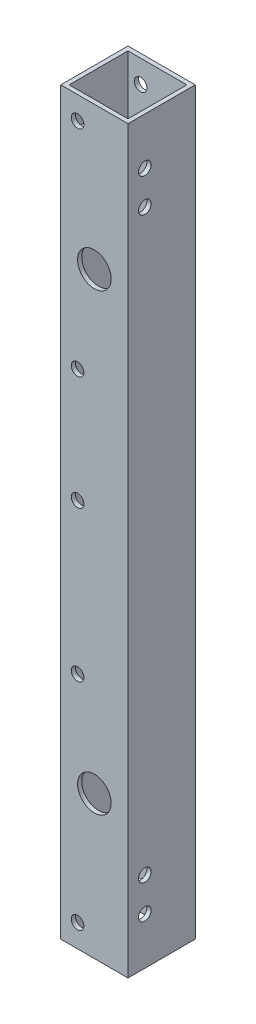
SolidWorks part; units mm, degrees
material "6061-T4 (SS)"
ref_plane "Front Plane" through (0, 0, 0) normal (0, 0, 1) x (1, 0, 0)
ref_plane "Top Plane" through (0, 0, 0) normal (0, 1, 0) x (1, 0, 0)
ref_plane "Right Plane" through (0, 0, 0) normal (1, 0, 0) x (0, 0, -1)
sketch "Sketch1" plane through (0, 0, 0) normal (0, 0, 1) x (1, 0, 0)
  line L1 (63.386, 102.0504) -> (88.786, 102.0504)
  line L2 (63.386, 102.0504) -> (63.386, -177.3496)
  line L3 (63.386, -177.3496) -> (88.786, -177.3496)
  line L4 (88.786, 102.0504) -> (88.786, -177.3496)
  dimension "D1" = 279.4
  dimension "D2" = 25.4
extrude "Boss-Extrude1" add sketch "Sketch1" along normal blind 25.4
sketch "Sketch2" plane through (0, 102.0504, 0) normal (0, 1, 0) x (1, 0, 0)
  line L0 (63.386, -25.4) -> (63.386, 0) construction
  line L1 (64.9735, -23.8125) -> (87.1985, -23.8125)
  line L2 (64.9735, -23.8125) -> (64.9735, -1.5875)
  line L3 (64.9735, -1.5875) -> (87.1985, -1.5875)
  line L4 (87.1985, -23.8125) -> (87.1985, -1.5875)
  line L5 (88.786, -25.4) -> (88.786, 0) construction
  line L6 (88.786, -25.4) -> (63.386, -25.4) construction
  line L7 (88.786, 0) -> (63.386, 0) construction
  dimension "D1" = 1.5875
  dimension "D2" = 1.5875
  dimension "D3" = 1.5875
  dimension "D4" = 1.5875
extrude "Cut-Extrude1" cut sketch "Sketch2" against normal blind 279.4
sketch "Sketch3" plane through (0, 0, 0) normal (0, 0, -1) x (-1, 0, 0)
  line L0 (-88.786, 102.0504) -> (-63.386, 102.0504) construction
  line L1 (-63.386, -177.3496) -> (-88.786, -177.3496) construction
  line L2 (-88.786, -177.3496) -> (-88.786, 102.0504) construction
  circle A0 centre (-76.086, 48.0754) radius 6.35
  circle A1 centre (-76.086, -123.3746) radius 6.35
  dimension "D1" = 53.975
  dimension "D2" = 53.975
  dimension "D3" = 12.7
  dimension "D4" = 12.7
  dimension "D5" = 12.7
  dimension "D6" = 12.7
extrude "Cut-Extrude2" cut sketch "Sketch3" against normal blind 25.4
sketch "Sketch4" plane through (88.786, 0, 0) normal (1, 0, 0) x (0, 0, -1)
  line L0 (-25.4, -177.3496) -> (-25.4, 102.0504) construction
  line L1 (-25.4, -177.3496) -> (0, -177.3496) construction
  line L2 (-55.2681, -37.6496) -> (45.2956, -37.6496) construction
  point P1 (-19.05, -159.5696)
  point P2 (-19.05, -146.8696)
  point P9 (-19.05, 71.5704)
  point P10 (-19.05, 84.2704)
  dimension "D2" = 6.35
  dimension "D3" = 6.35
  dimension "D5" = 17.78
  dimension "D6" = 30.48
  dimension "D7" = 139.7
sketch "Sketch7" plane through (0, 0, 0) normal (0, 0, -1) x (-1, 0, 0)
  line L0 (-88.786, 102.0504) -> (-63.386, 102.0504) construction
  line L1 (-63.386, 102.0504) -> (-63.386, -177.3496) construction
  line L2 (-88.786, -177.3496) -> (-88.786, 102.0504) construction
  line L3 (-63.386, -177.3496) -> (-88.786, -177.3496) construction
  point P0 (-69.736, 93.4144)
  point P5 (-69.736, 12.2614)
  point P8 (-69.736, -30.6646)
  point P9 (-69.736, -87.4336)
  point P12 (-69.736, -168.7136)
  dimension "D1" = 8.636
  dimension "D2" = 6.35
  dimension "D3" = 89.789
  dimension "D4" = 19.05
  dimension "D5" = 132.715
  dimension "D6" = 19.05
  dimension "D7" = 89.916
  dimension "D8" = 19.05
  dimension "D9" = 8.636
  dimension "D10" = 19.05
hole_wizard "3/16 (0.1875) Diameter Hole2" positions "Sketch8" profile "Sketch9" hole size "3/16" standard "ANSI Inch" end condition through all
sketch "Sketch8" plane through (0, 0, 0) normal (0, 0, -1) x (-1, 0, 0)
  point P0 (-69.736, 93.4144)
  point P3 (-69.736, 12.2614)
  point P6 (-69.736, -30.6646)
  point P9 (-69.736, -87.4336)
  point P12 (-69.736, -168.7136)
sketch "Sketch9" plane through (69.736, 93.4144, 0) normal (1, 0, 0) x (0, 1, 0)
  line L0 (0, 0) -> (0, 25.4)
  line L1 (0, 25.4) -> (2.3812, 25.4)
  line L2 (2.3812, 25.4) -> (2.3812, 0)
  line L5 (2.3812, 0) -> (0, 0)
  line L11 (0, -6.35) -> (0, 107.95) construction
  dimension "Thru Hole Dia." = 4.7625
  dimension "Thru Hole Depth" = 25.4
hole_wizard "3/16 (0.1875) Diameter Hole3" positions "Sketch12" profile "Sketch11" hole size "3/16" standard "ANSI Inch" end condition through all
sketch "Sketch12" plane through (88.786, 0, 0) normal (1, 0, 0) x (0, 0, -1)
  point P0 (-19.05, -159.5696)
  point P3 (-19.05, -146.8696)
  point P6 (-19.05, 71.5704)
  point P9 (-19.05, 84.2704)
sketch "Sketch11" plane through (88.786, -159.5696, 19.05) normal (0, 1, 0) x (0, 0, -1)
  line L0 (0, 0) -> (0, 25.4)
  line L1 (0, 25.4) -> (2.3812, 25.4)
  line L2 (2.3812, 25.4) -> (2.3812, 0)
  line L5 (2.3812, 0) -> (0, 0)
  line L11 (0, -6.35) -> (0, 107.95) construction
  dimension "Thru Hole Dia." = 4.7625
  dimension "Thru Hole Depth" = 25.4
